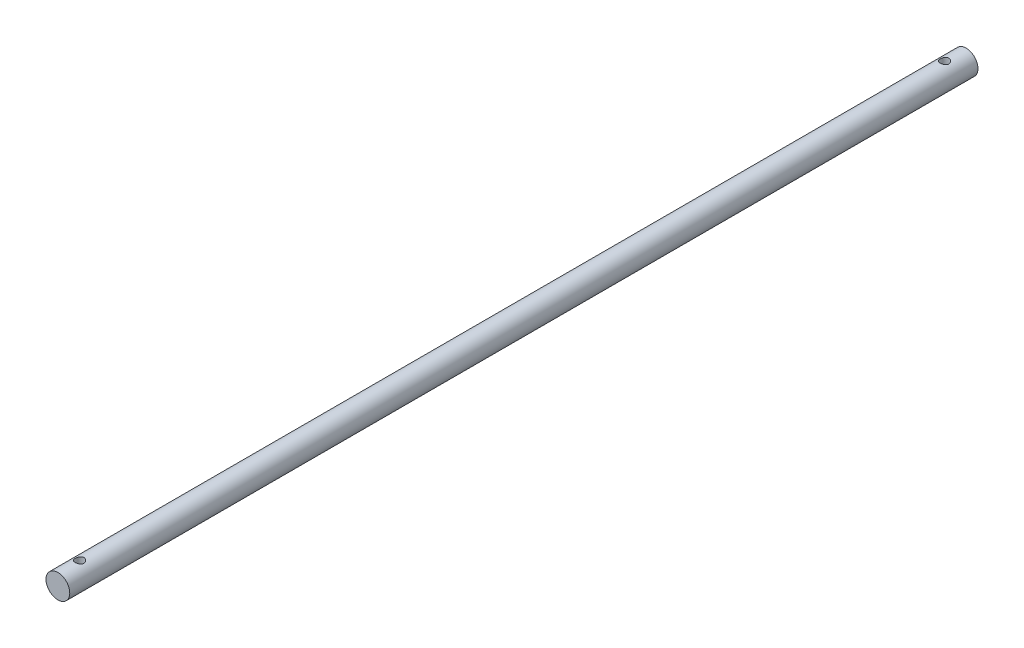
SolidWorks part; units mm, degrees
ref_plane "Front Plane" through (0, 0, 0) normal (0, 0, 1) x (1, 0, 0)
ref_plane "Top Plane" through (0, 0, 0) normal (0, 1, 0) x (1, 0, 0)
ref_plane "Right Plane" through (0, 0, 0) normal (1, 0, 0) x (0, 0, -1)
sketch "Sketch1" plane through (0, 0, 0) normal (0, 0, 1) x (1, 0, 0)
  circle A0 centre (0, 0) radius 2.75
  dimension "D1" = 5.5
extrude "Boss-Extrude1" add sketch "Sketch1" along normal blind 210
sketch "Sketch2" plane through (0, 0, 0) normal (0, 1, 0) x (1, 0, 0)
  line L0 (0, 0) -> (0, -11.721) construction
  circle A0 centre (0, -5) radius 1
  point P3 (0, -5)
  dimension "D2" = 2
  dimension "D1" = 5
extrude "Cut-Extrude1" cut sketch "Sketch2" against normal through all both and the other way through all
sketch "Sketch3" plane through (0, 0, 0) normal (0, 1, 0) x (1, 0, 0)
  line L0 (0, -210) -> (0, -201.4753) construction
  line L1 (-2.75, -210) -> (2.75, -210) construction
  circle A0 centre (0, -205) radius 1
  dimension "D2" = 2
  dimension "D1" = 5
extrude "Cut-Extrude2" cut sketch "Sketch3" against normal through all both and the other way through all contours A0
